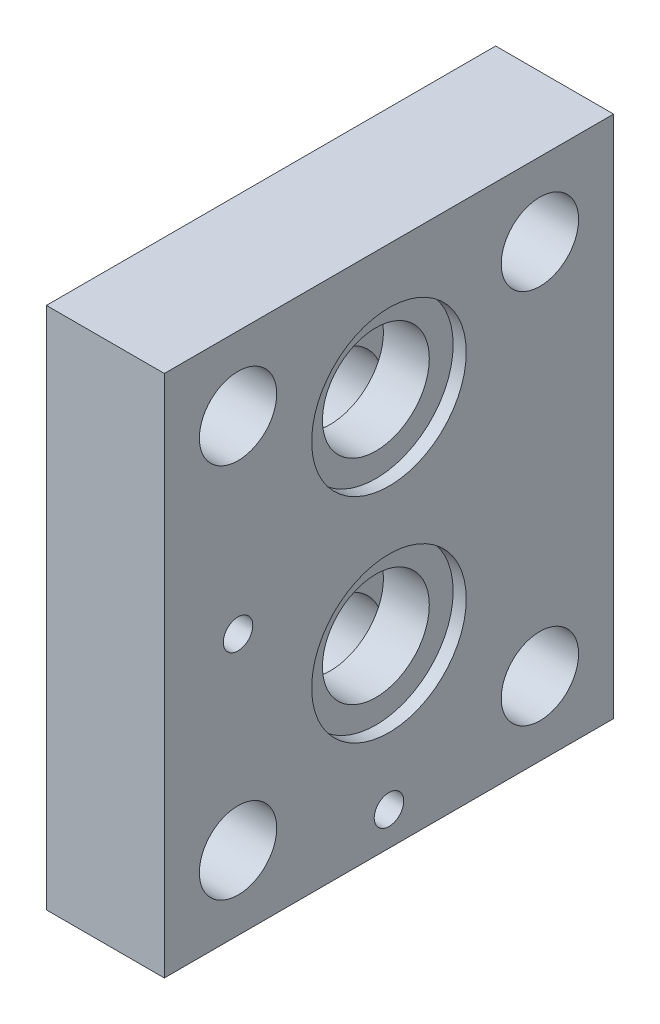
SolidWorks part; units mm, degrees
ref_plane "Front Plane" through (0, 0, 0) normal (1, 0, 0) x (0, 1, 0)
ref_plane "Top Plane" through (0, 0, 0) normal (0, 0, 1) x (0, 1, 0)
ref_plane "Right Plane" through (0, 0, 0) normal (0, 1, 0) x (-1, 0, 0)
sketch "Sketch1" plane through (0, 0, 0) normal (1, 0, 0) x (0, 1, 0)
  line L1 (0, 0) -> (112.776, 0)
  line L2 (0, 0) -> (0, 96.774)
  line L3 (0, 96.774) -> (112.776, 96.774)
  line L4 (112.776, 0) -> (112.776, 96.774)
extrude "Boss-Extrude1" add sketch "Sketch1" along normal blind 25.4
sketch "Sketch2" plane through (0, 0, 0) normal (1, 0, 0) x (0, 1, 0)
  circle A0 centre (15.875, 15.875) radius 8.3344
extrude "Cut-Extrude2" cut sketch "Sketch2" along normal through all
sketch "Sketch3" plane through (0, 0, 0) normal (1, 0, 0) x (0, 1, 0)
  circle A0 centre (96.901, 15.875) radius 8.3344
  circle A1 centre (15.875, 80.899) radius 8.3344
  circle A2 centre (96.901, 80.899) radius 8.3344
extrude "Cut-Extrude4" cut sketch "Sketch3" along normal through all
sketch "Sketch4" plane through (0, 0, 0) normal (1, 0, 0) x (0, 1, 0)
  circle A0 centre (28.575, 48.387) radius 11.5094
extrude "Cut-Extrude6" cut sketch "Sketch4" along normal blind 12.7
sketch "Sketch5" plane through (0, 0, 0) normal (1, 0, 0) x (0, 1, 0)
  circle A0 centre (74.549, 48.387) radius 11.5094
extrude "Cut-Extrude8" cut sketch "Sketch5" along normal blind 12.7
sketch "Sketch6" plane through (0, 0, 0) normal (1, 0, 0) x (0, 1, 0)
  circle A0 centre (38.227, 48.387) radius 11.5094
extrude "Cut-Extrude10" cut sketch "Sketch6" against normal blind 12.7 from offset 25.4
sketch "Sketch7" plane through (0, 0, 0) normal (1, 0, 0) x (0, 1, 0)
  circle A0 centre (84.201, 48.387) radius 11.5094
extrude "Cut-Extrude12" cut sketch "Sketch7" against normal blind 12.7 from offset 25.4
sketch "Sketch8" plane through (0, 0, 0) normal (1, 0, 0) x (0, 1, 0)
  circle A0 centre (38.227, 48.387) radius 16.6497
extrude "Cut-Extrude14" cut sketch "Sketch8" against normal blind 2.8194 from offset 25.4
sketch "Sketch9" plane through (0, 0, 0) normal (1, 0, 0) x (0, 1, 0)
  circle A0 centre (84.201, 48.387) radius 16.6497
extrude "Cut-Extrude16" cut sketch "Sketch9" against normal blind 2.8194 from offset 25.4
sketch "Sketch10" plane through (0, 0, 0) normal (1, 0, 0) x (0, 1, 0)
  circle A0 centre (105.537, 48.387) radius 3.5719
extrude "Cut-Extrude18" cut sketch "Sketch10" along normal blind 7.874
sketch "Sketch11" plane through (0, 0, 0) normal (1, 0, 0) x (0, 1, 0)
  circle A0 centre (56.515, 15.875) radius 3.5719
extrude "Cut-Extrude20" cut sketch "Sketch11" along normal blind 7.874
sketch "Sketch12" plane through (0, 0, 0) normal (1, 0, 0) x (0, 1, 0)
  circle A0 centre (7.239, 48.387) radius 3.175
extrude "Cut-Extrude22" cut sketch "Sketch12" against normal blind 7.874 from offset 25.4
sketch "Sketch13" plane through (0, 0, 0) normal (1, 0, 0) x (0, 1, 0)
  circle A0 centre (56.261, 80.899) radius 3.175
extrude "Cut-Extrude24" cut sketch "Sketch13" against normal blind 7.874 from offset 25.4
